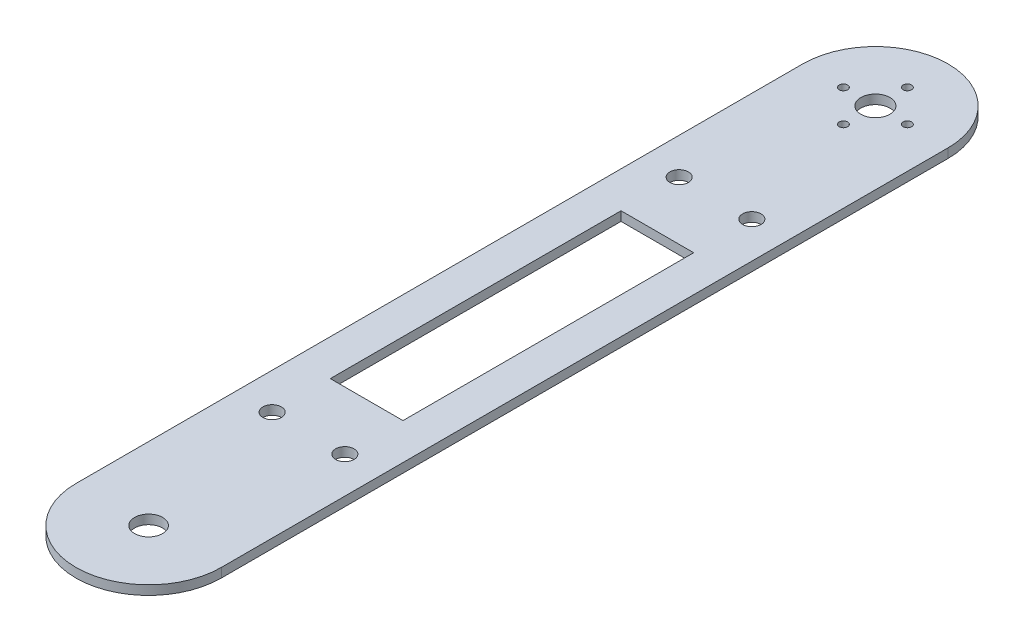
SolidWorks part; units mm, degrees
ref_plane "Front" through (0, 0, 0) normal (0, 0, 1) x (1, 0, 0)
ref_plane "Top" through (0, 0, 0) normal (0, 1, 0) x (1, 0, 0)
ref_plane "Right" through (0, 0, 0) normal (1, 0, 0) x (0, 0, -1)
sketch "Sketch1" plane through (0, 0, 0) normal (0, 1, 0) x (1, 0, 0)
  line L1 (0, 0) -> (50, 0)
  line L2 (0, 0) -> (0, -300)
  line L3 (0, -300) -> (50, -300)
  line L4 (50, 0) -> (50, -300)
  dimension "D1" = 300
  dimension "D2" = 50
extrude "Boss-Extrude1" add sketch "Sketch1" along normal blind 3.175
sketch "Sketch2" plane through (0, 3.175, 0) normal (0, 1, 0) x (1, 0, 0)
  line L0 (0, -25) -> (0, 0)
  line L1 (0, 0) -> (50, 0)
  line L2 (50, 0) -> (50, -25)
  line L3 (0, -275) -> (0, -300)
  line L4 (0, -300) -> (50, -300)
  line L5 (50, -300) -> (50, -275)
  circle A0 centre (25, -25) radius 25
  circle A1 centre (25, -275) radius 25
  line M1 (0, 0) -> (0, -300)
  line M2 (0, -300) -> (50, -300)
  line M3 (50, -300) -> (50, 0)
  line M4 (50, 0) -> (0, 0)
extrude "Cut-Extrude1" cut sketch "Sketch2" against normal blind 6.35 contours A0 M3 M4 | A0 L1 M1 | A1 L4 M3 | A1 M1 M2
sketch "Sketch3" plane through (0, 3.175, 0) normal (0, 1, 0) x (1, 0, 0)
  line L0 (25, 0) -> (25, -300) construction
  line L1 (0, -25) -> (50, -25) construction
  arc A0 (50, -25) -> (0, -25) centre (25, -25) ccw construction
  circle A1 centre (25, -25) radius 5
  circle A2 centre (25, -275) radius 4.82
  circle A3 centre (25, -14) radius 1.025
  circle A4 centre (14, -25) radius 1.025
  circle A5 centre (25, -36) radius 1.025
  circle A6 centre (36, -25) radius 1.025
  arc A7 (0, -275) -> (50, -275) centre (25, -275) ccw construction
  dimension "D1" = 2.05
  dimension "D2" = 9.64
  dimension "D3" = 10
  dimension "D4" = 11
  dimension "D6" = 11
  dimension "D7" = 11
  dimension "D5" = 11
extrude "Cut-Extrude2" cut sketch "Sketch3" against normal blind 6.35
sketch "Sketch4" plane through (0, 3.175, 0) normal (0, 1, 0) x (1, 0, 0)
  line L0 (25, 0) -> (25, -300) construction
  line L1 (0, -150) -> (50, -150) construction
  line L2 (12.5, -100) -> (37.5, -100)
  line L3 (12.5, -100) -> (12.5, -200)
  line L4 (12.5, -200) -> (37.5, -200)
  line L5 (37.5, -100) -> (37.5, -200)
  line L6 (0, -25) -> (0, -275) construction
  line L7 (50, -275) -> (50, -25) construction
  circle A0 centre (12.5, -80) radius 3.175
  circle A1 centre (12.5, -220) radius 3.175
  arc A2 (50, -25) -> (0, -25) centre (25, -25) ccw construction
  arc A3 (0, -275) -> (50, -275) centre (25, -275) ccw construction
  circle A4 centre (37.5, -220) radius 3.175
  circle A5 centre (37.5, -80) radius 3.175
  dimension "D3" = 6.35
  dimension "D4" = 70
  dimension "D5" = 12.5
  dimension "D1" = 25
  dimension "D2" = 100
extrude "Cut-Extrude3" cut sketch "Sketch4" against normal blind 6.35
hole_wizard "M2.5 Clearance Hole1" positions "Sketch8" profile "Sketch7" hole size "M2.5" standard "ANSI Metric" end condition through all
sketch "Sketch8" plane through (0, 3.175, 0) normal (0, 1, 0) x (1, 0, 0)
  point P0 (14, -25)
  point P3 (25, -14)
  point P6 (36, -25)
  point P9 (25, -36)
sketch "Sketch7" plane through (14, 3.175, 25) normal (1, 0, 0) x (0, 0, 1)
  line L0 (0, 0) -> (0, 3.175)
  line L1 (0, 3.175) -> (1.45, 3.175)
  line L2 (1.45, 3.175) -> (1.45, 0)
  line L5 (1.45, 0) -> (0, 0)
  line L11 (0, -6.35) -> (0, 107.95) construction
  dimension "Thru Hole Dia." = 2.9
  dimension "Thru Hole Depth" = 3.175
